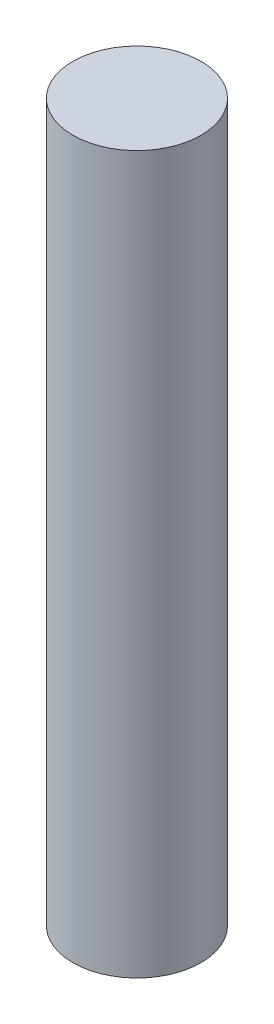
SolidWorks part; units mm, degrees
ref_plane "前视基准面" through (0, 0, 0) normal (0, 0, 1) x (1, 0, 0)
ref_plane "上视基准面" through (0, 0, 0) normal (0, 1, 0) x (1, 0, 0)
ref_plane "右视基准面" through (0, 0, 0) normal (1, 0, 0) x (0, 0, -1)
other "Configuration Table"
sketch "草图2" plane through (0, 312.0019, 0) normal (0, 1, 0) x (-0.7676, 0, 0.641)
  circle A0 centre (0, 0) radius 29.5
  dimension "D1" = 59
extrude "凸台-拉伸1" add sketch "草图2" along normal blind 330
